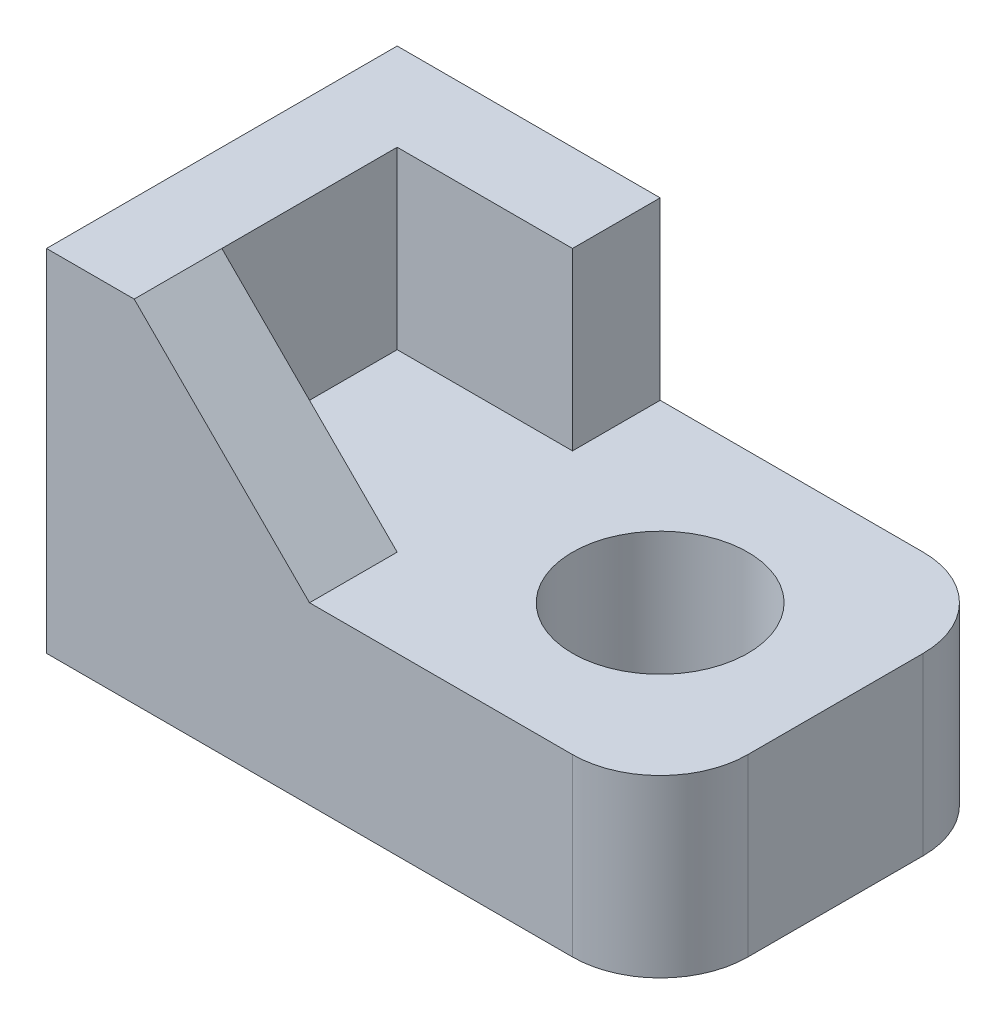
SolidWorks part; units mm, degrees
ref_plane "前基準面" through (0, 0, 0) normal (0, 0, 1) x (1, 0, 0)
ref_plane "上基準面" through (0, 0, 0) normal (0, 1, 0) x (1, 0, 0)
ref_plane "右基準面" through (0, 0, 0) normal (1, 0, 0) x (0, 0, -1)
sketch "草圖1" plane through (0, 0, 0) normal (0, 1, 0) x (1, 0, 0)
  line L1 (10, 10) -> (-25, 10)
  line L2 (10, 10) -> (10, -10)
  line L3 (10, -10) -> (-25, -10)
  line L4 (-25, 10) -> (-25, -10)
  circle A0 centre (0, 0) radius 5
  point P7 (10, 0)
  dimension "D2" = 10
  dimension "D1" = 10
  dimension "D3" = 35
  dimension "D4" = 20
extrude "填料-伸長1" add sketch "草圖1" along normal blind 10
sketch "草圖2" plane through (0, 10, 0) normal (0, 1, 0) x (1, 0, 0)
  line L0 (10, 10) -> (-25, 10) construction
  line L1 (-25, -10) -> (-20, -10)
  line L2 (-25, -10) -> (-25, 10)
  line L3 (-25, 10) -> (-20, 10)
  line L4 (-20, -10) -> (-20, 10)
  line L6 (-10, 10) -> (-25, 10)
  line L7 (-10, 10) -> (-10, 5)
  line L8 (-10, 5) -> (-25, 5)
  line L9 (-25, 10) -> (-25, 5)
  line M5 (10, 10) -> (-25, 10)
  line M6 (-25, 10) -> (-25, -10)
  line M7 (-25, -10) -> (10, -10)
  dimension "D1" = 5
  dimension "D2" = 15
  dimension "D3" = 5
extrude "填料-伸長2" add sketch "草圖2" along normal blind 10 contours L8 L4 M5 M6 | L4 L8 L2 M7 | L8 L7 L4 M5
sketch "草圖3" plane through (0, 0, 10) normal (0, 0, 1) x (1, 0, 0)
  line L0 (-20, 20) -> (-20, 10) construction
  line L1 (-20, 20) -> (-20, 10)
  line L2 (-20, 20) -> (-10, 10)
  line L3 (-10, 10) -> (-20, 10)
  line L4 (-20, 10) -> (-19.8919, 10.0207)
extrude "填料-伸長3" add sketch "草圖3" against normal blind 5
fillet "圓角1" radius 5 2 edges at (10, 5, -10) (10, 5, 10)
